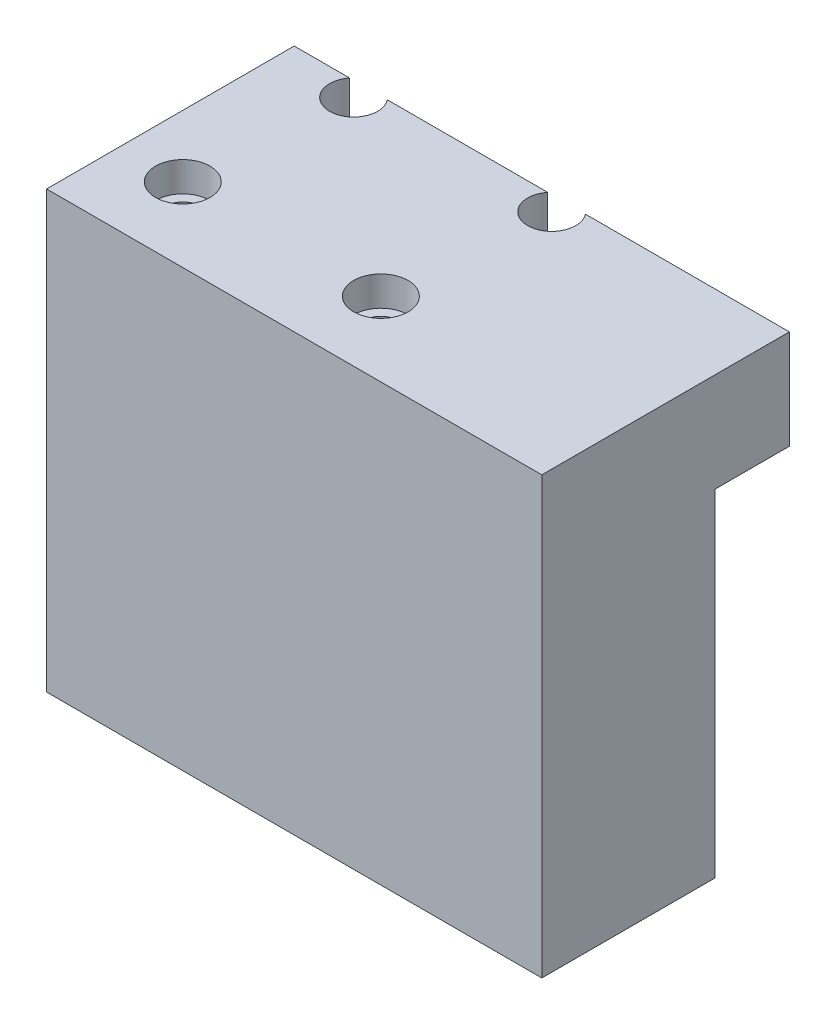
SolidWorks part; units mm, degrees
material "S45C表面镀硬铬"
ref_plane "前基準面" through (0, 0, 0) normal (0, 0, 1) x (1, 0, 0)
ref_plane "上基準面" through (0, 0, 0) normal (0, 1, 0) x (1, 0, 0)
ref_plane "右基準面" through (0, 0, 0) normal (1, 0, 0) x (0, 0, -1)
sketch "草图1" plane through (0, 0, 0) normal (0, 0, 1) x (1, 0, 0)
  line L1 (0, 0) -> (100, 0)
  line L2 (0, 0) -> (0, 88)
  line L3 (0, 88) -> (100, 88)
  line L4 (100, 0) -> (100, 88)
  dimension "D1" = 100
  dimension "D2" = 88
extrude "凸台-拉伸1" add sketch "草图1" along normal blind 50
sketch "草图2" plane through (0, 0, 0) normal (-1, 0, 0) x (0, 0, 1)
  line L0 (50, 88) -> (0, 88) construction
  line L1 (0, 0) -> (15, 0)
  line L2 (0, 0) -> (0, 68)
  line L3 (0, 68) -> (15, 68)
  line L4 (15, 0) -> (15, 68)
  dimension "D1" = 20
  dimension "D2" = 15
extrude "切除-拉伸1" cut sketch "草图2" against normal through all
sketch "草图4" plane through (0, 88, 0) normal (0, 1, 0) x (1, 0, 0)
  line L0 (0, -50) -> (0, 0) construction
  line L1 (100, 0) -> (0, 0) construction
  circle A0 centre (15, -3) radius 4.85
  circle A1 centre (55, -3) radius 4.85
  dimension "D1" = 9.7
  dimension "D2" = 15
  dimension "D3" = 40
  dimension "D4" = 3
extrude "切除-拉伸3" cut sketch "草图4" against normal through all
hole_wizard "M6 六角凹头螺钉的柱形沉头孔1" positions "草图8" profile "草图7" counterbore size "M6" standard "ISO" end condition through all
sketch "草图8" plane through (0, 88, 0) normal (0, 1, 0) x (-1, 0, 0)
  line L1 (-100, 50) -> (0, 50) construction
  line L2 (0, 50) -> (0, 0) construction
  point P0 (-12.5, 35)
  point P1 (-52.5, 35)
  dimension "D1" = 40
  dimension "D2" = 15
  dimension "D3" = 12.5
sketch "草图7" plane through (12.5, 88, 35) normal (1, 0, 0) x (0, 0, 1)
  line L0 (0, 0) -> (0, 88)
  line L1 (0, 88) -> (3.5, 88)
  line L3 (3.5, 88) -> (3.5, 6)
  line L4 (3.5, 6) -> (5.5, 6)
  line L5 (5.5, 6) -> (5.5, 0)
  line L7 (5.5, 0) -> (0, 0)
  line L11 (0, -6.35) -> (0, 107.95) construction
  dimension "通孔孔直径" = 7
  dimension "通孔孔深度" = 88
  dimension "柱形沉头孔直径" = 11
  dimension "柱形沉头孔深度" = 6
